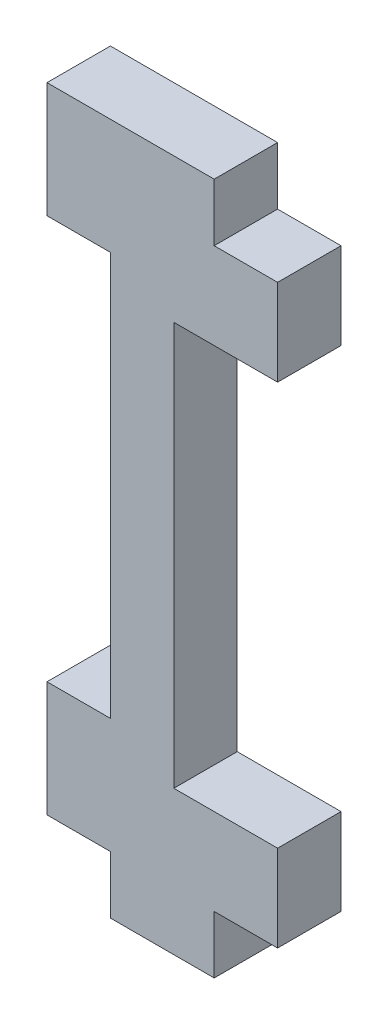
SolidWorks part; units mm, degrees
material "ﾁｰｸ材"
ref_plane "正面" through (0, 0, 0) normal (0, 0, 1) x (1, 0, 0)
ref_plane "平面" through (0, 0, 0) normal (0, 1, 0) x (1, 0, 0)
ref_plane "右側面" through (0, 0, 0) normal (1, 0, 0) x (0, 0, -1)
sketch "ｽｹｯﾁ1" plane through (0, 0, 0) normal (0, 0, 1) x (1, 0, 0)
  line L1 (10, -60) -> (-10, -60)
  line L2 (10, -60) -> (10, 0)
  line L3 (10, 0) -> (-10, 0)
  line L4 (-10, -60) -> (-10, 0)
  line L5 (10, -60) -> (-10, 0) construction
  line L6 (10, 0) -> (-10, -60) construction
  point P0 (0, -30)
  point P5 (13.5, -28.25)
  point P6 (0, 0)
  point P8 (0, -29.1559)
  dimension "D1" = 20
  dimension "60" = 60
extrude "ﾎﾞｽ - 押し出し1" add sketch "ｽｹｯﾁ1" along normal blind 5.5
sketch "ｽｹｯﾁ3" plane through (0, 0, 5.5) normal (0, 0, 1) x (1, 0, 0)
  line L0 (-10, 0) -> (-10, -60) construction
  line L1 (-10, -10) -> (-4.5, -10)
  line L2 (-10, -10) -> (-10, -45)
  line L3 (-10, -45) -> (-4.5, -45)
  line L4 (-4.5, -10) -> (-4.5, -45)
  line L7 (-10, -55) -> (-4.5, -55)
  line L8 (-10, -55) -> (-10, -60)
  line L9 (-10, -60) -> (-4.5, -60)
  line L10 (-4.5, -55) -> (-4.5, -60)
  line L11 (10, 0) -> (-10, 0) construction
  line L12 (10, -60) -> (10, 0) construction
  line L13 (1, -47.5) -> (10, -47.5)
  line L14 (1, -47.5) -> (1, -12.5)
  line L15 (1, -12.5) -> (10, -12.5)
  line L16 (10, -47.5) -> (10, -12.5)
  line L17 (10, 0) -> (-10, 0) construction
  line L18 (10, -60) -> (4.5, -60)
  line L19 (10, -60) -> (10, -55)
  line L20 (10, -55) -> (4.5, -55)
  line L21 (4.5, -60) -> (4.5, -55)
  line L22 (10, -60) -> (10, 0) construction
  line L23 (10, 0) -> (4.5, 0)
  line L24 (10, 0) -> (10, -5)
  line L25 (10, -5) -> (4.5, -5)
  line L26 (4.5, 0) -> (4.5, -5)
  point P29 (10, 0)
  dimension "D1" = 5.5
  dimension "D2" = 35
  dimension "D3" = 5.5
  dimension "D4" = 5
  dimension "D5" = 10
  dimension "D6" = 10
  dimension "D7" = 5
  dimension "D8" = 5.5
  dimension "D9" = 9
  dimension "D10" = 35
  dimension "D11" = 12.5
  dimension "D12" = 5.5
  dimension "D13" = 5
extrude "ｶｯﾄ - 押し出し1" cut sketch "ｽｹｯﾁ3" against normal through all
